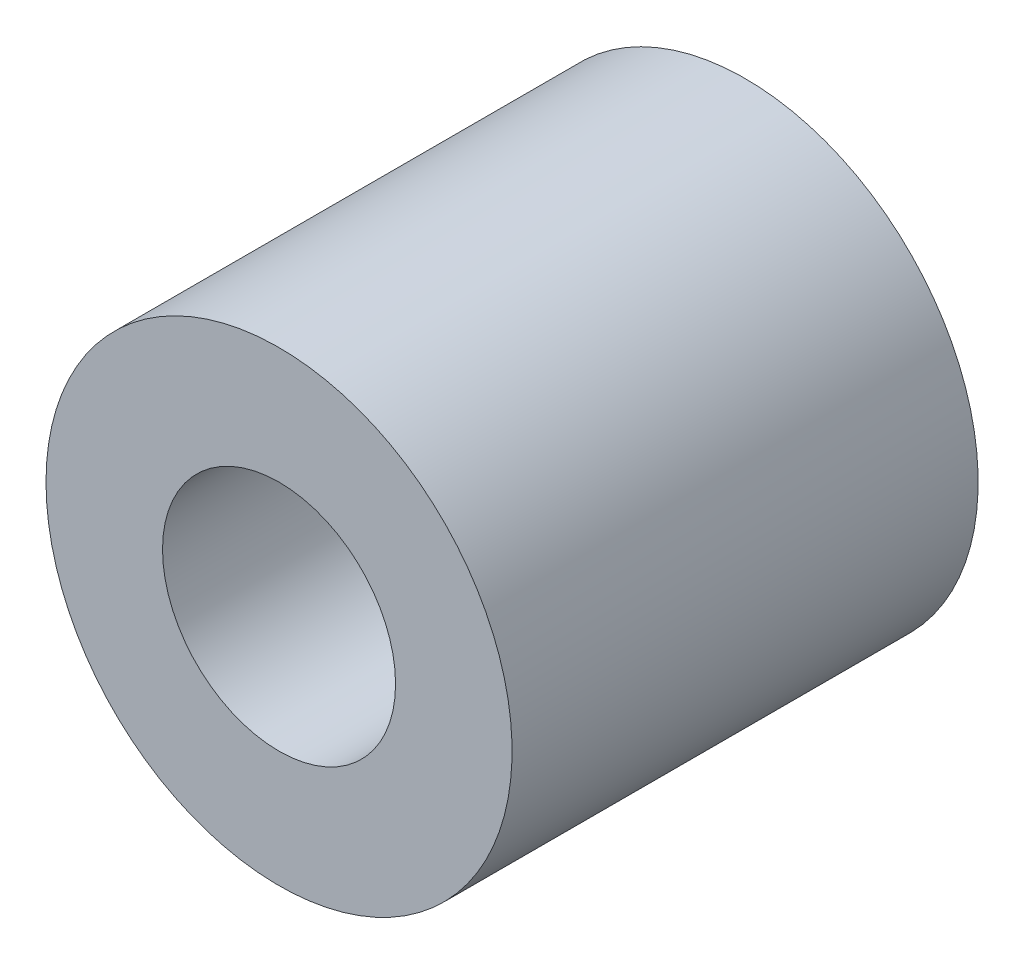
SolidWorks part; units mm, degrees
ref_plane "Front Plane" through (0, 0, 0) normal (0, 0, 1) x (1, 0, 0)
ref_plane "Top Plane" through (0, 0, 0) normal (0, 1, 0) x (1, 0, 0)
ref_plane "Right Plane" through (0, 0, 0) normal (1, 0, 0) x (0, 0, -1)
sketch "Sketch1" plane through (0, 0, 0) normal (0, 0, 1) x (1, 0, 0)
  circle A0 centre (0, 0) radius 4.7625
  circle A1 centre (0, 0) radius 9.525
  dimension "D1" = 9.525
  dimension "D2" = 19.05
extrude "Boss-Extrude1" add sketch "Sketch1" along normal mid plane 19.05
